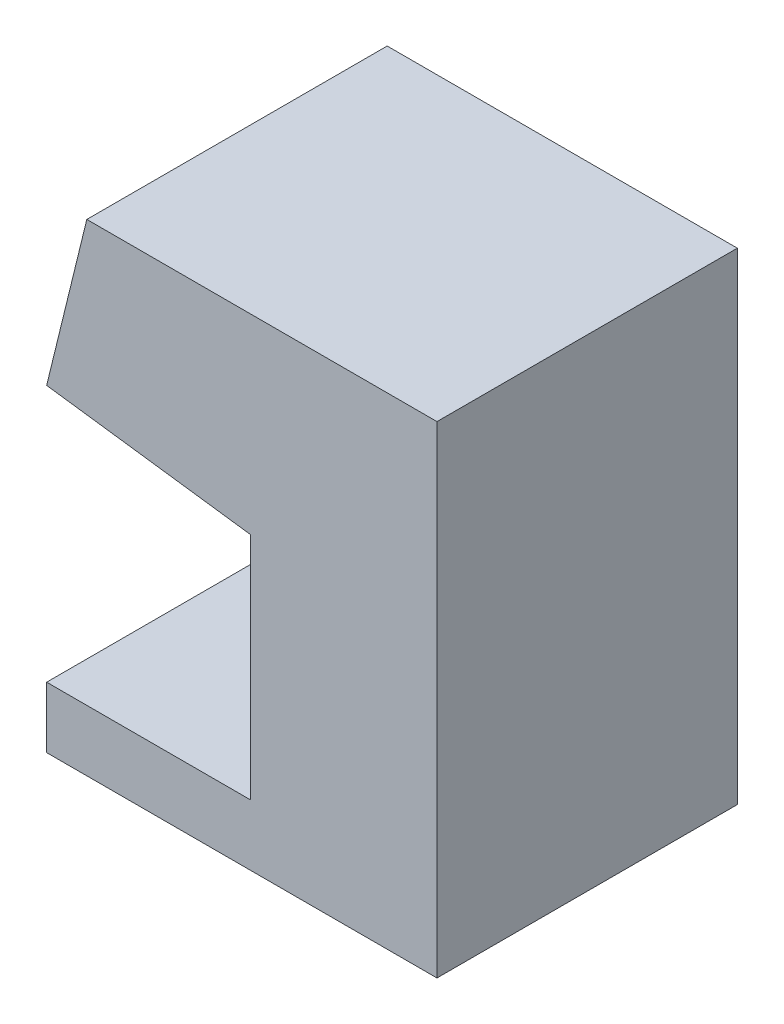
SolidWorks part; units mm, degrees
ref_plane "Front Plane" through (0, 0, 0) normal (0, 0, 1) x (1, 0, 0)
ref_plane "Top Plane" through (0, 0, 0) normal (0, 1, 0) x (1, 0, 0)
ref_plane "Right Plane" through (0, 0, 0) normal (1, 0, 0) x (0, 0, -1)
sketch "Sketch1" plane through (0, 0, 0) normal (0, 0, 1) x (1, 0, 0)
  line L0 (0, 0) -> (243, 0)
  line L1 (243, 0) -> (243, 300)
  line L2 (243, 300) -> (25, 300)
  line L5 (127, 181) -> (127, 38)
  line L6 (127, 38) -> (0, 38)
  line L7 (0, 38) -> (0, 0)
  line L8 (0, 198) -> (127, 181)
  line L10 (25, 300) -> (0, 198)
  dimension "D1" = 300
  dimension "D2" = 218
  dimension "D3" = 38
  dimension "D5" = 143
  dimension "D6" = 127
extrude "Boss-Extrude2" add sketch "Sketch1" along normal blind 187
